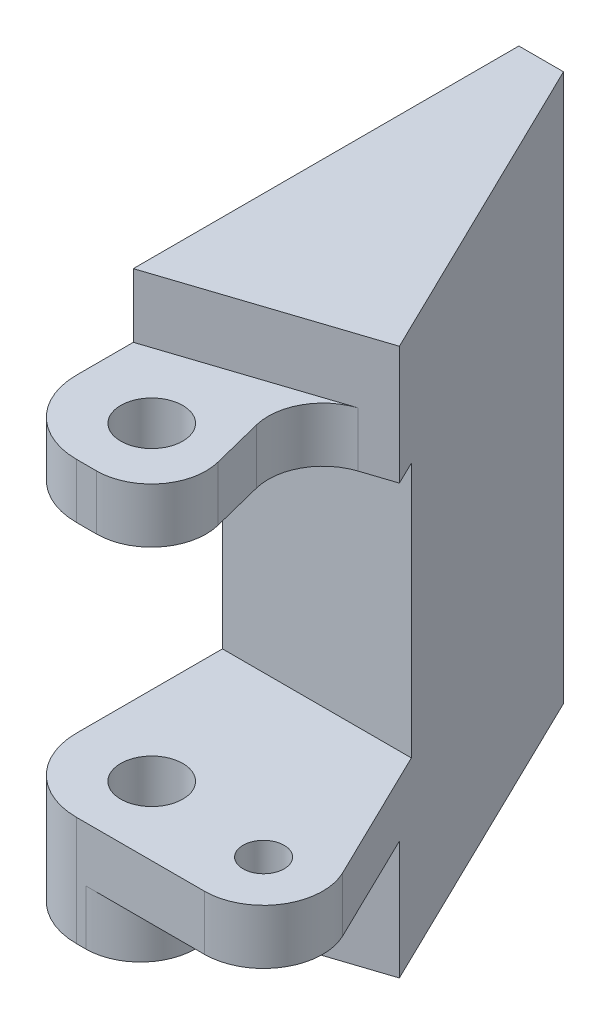
SolidWorks part; units mm, degrees
ref_plane "Front Plane" through (0, 0, 0) normal (0, 0, 1) x (1, 0, 0)
ref_plane "Top Plane" through (0, 0, 0) normal (0, 1, 0) x (1, 0, 0)
ref_plane "Right Plane" through (0, 0, 0) normal (1, 0, 0) x (0, 0, -1)
sketch "Sketch1" plane through (0, 0, 0) normal (0, 1, 0) x (1, 0, 0)
  line L0 (47.2297, 219.0186) -> (732.563, 219.0186) construction
  line L1 (-67.4173, 89.7545) -> (-64.9698, 89.7545)
  line L2 (-67.4173, 89.7545) -> (-67.4173, 61.5)
  line L3 (-67.4173, 61.5) -> (-56.4024, 61.5)
  line L4 (-64.9698, 89.7545) -> (-53.4866, 66.162)
  circle A0 centre (-63.067, 65.2736) radius 1.7
  circle A1 centre (-56.4024, 64.7428) radius 1.125
  arc A2 (-56.4024, 61.5) -> (-53.4866, 66.162) centre (-56.4024, 64.7428) ccw
extrude "Boss-Extrude1" add sketch "Sketch1" along normal blind 30
sketch "Sketch2" plane through (0, 0, 0) normal (0, 1, 0) x (1, 0, 0)
  line L0 (-67.2577, 68.6656) -> (-56.3609, 72.247) construction
sketch "Sketch4" plane through (0, 0, 0) normal (0, -1, 0) x (-1, 0, 0)
  line L1 (56.3609, 72.247) -> (67.2577, 68.6656)
  line L2 (67.2577, 68.6656) -> (67.5649, 68.5647)
  line L3 (67.5649, 68.5647) -> (68.0749, 60.6651)
  line L4 (68.0749, 60.6651) -> (50.6751, 61.3033)
  line L5 (50.6751, 61.3033) -> (50.3236, 66.7482)
  line L6 (50.3236, 66.7482) -> (56.3609, 72.247)
extrude "Cut-Extrude1" cut sketch "Sketch4" against normal blind 3.5
sketch "Sketch5" plane through (0, 30, 0) normal (0, 1, 0) x (1, 0, 0)
  line L0 (-56.3609, 72.247) -> (-67.2577, 68.6656)
  line L1 (-67.2577, 68.6656) -> (-69.834, 67.8189)
  line L2 (-69.834, 67.8189) -> (-69.834, 60.4734)
  line L3 (-69.834, 60.4734) -> (-51.5314, 60.4734)
  line L4 (-51.5314, 60.4734) -> (-50.581, 66.5719)
  line L5 (-50.581, 66.5719) -> (-56.3609, 72.247)
extrude "Cut-Extrude2" cut sketch "Sketch5" against normal blind 3.5
fillet "Fillet1" radius 4 1 edges at (-67.4173, 15, -61.5)
sketch "Sketch6" plane through (-67.4173, 0, 0) normal (-1, 0, 0) x (0, 0, 1)
  line L0 (-68.6132, 3.5) -> (-65.5, 3.5) construction
  line L1 (-73.5, 9.5) -> (-56.6072, 9.5)
  line L2 (-73.5, 9.5) -> (-73.5, 23.5)
  line L3 (-73.5, 23.5) -> (-56.6072, 23.5)
  line L4 (-56.6072, 9.5) -> (-56.6072, 23.5)
  line L5 (-68.6132, 26.5) -> (-65.5, 26.5) construction
  line L6 (-65.5, 3.5) -> (-65.5, 26.5) construction
  dimension "D1" = 6
  dimension "D2" = 3
  dimension "D3" = 8
extrude "Cut-Extrude3" cut sketch "Sketch6" against normal through all
sketch "Sketch7" plane through (0, 3.5, 0) normal (0, -1, 0) x (-1, 0, 0)
  line L0 (56.4363, 72.2222) -> (53.4866, 66.162)
  line L1 (53.4866, 66.162) -> (50.723, 60.484)
  line L2 (50.723, 60.484) -> (56.4024, 61.5)
  line L3 (56.4024, 61.5) -> (59.9098, 61.5)
  line L4 (63.4173, 61.5) -> (56.4024, 61.5) construction
  line L5 (59.9098, 61.5) -> (59.9098, 70.201)
  line L6 (59.9098, 70.201) -> (59.9098, 71.0806)
  line L7 (67.4173, 68.6132) -> (56.4363, 72.2222) construction
  line L8 (59.9098, 71.0806) -> (56.4363, 72.2222)
extrude "Cut-Extrude4" cut sketch "Sketch7" against normal blind 3
fillet "Fillet2" radius 3 1 edges at (-59.9098, 5, -61.5)
fillet "Fillet3" radius 3 1 edges at (-59.9098, 5, -71.0806)
sketch "Sketch8" plane through (0, 26.5, 0) normal (0, 1, 0) x (1, 0, 0)
  line L0 (-59.6114, 71.1787) -> (-60.8026, 70.7872)
  line L1 (-63.4173, 61.5) -> (-56.4024, 61.5) construction
  line L2 (-56.4363, 72.2222) -> (-67.4173, 68.6132) construction
  line L3 (-59.6114, 71.1787) -> (-56.4363, 72.2222)
  line L4 (-56.4363, 72.2222) -> (-50.8562, 63.6356)
  line L5 (-50.8562, 63.6356) -> (-56.1206, 59.6372)
  line L6 (-58.4643, 61.5) -> (-56.1206, 59.6372)
  line L7 (-60.8026, 70.7872) -> (-58.4643, 61.5)
extrude "Cut-Extrude7" cut sketch "Sketch8" against normal blind 10
fillet "Fillet4" radius 3 1 edges at (-58.4643, 25, -61.5)
fillet "Fillet5" radius 3 1 edges at (-60.8026, 25, -70.7872)
equation "\"3.5.00mm\"=3"
